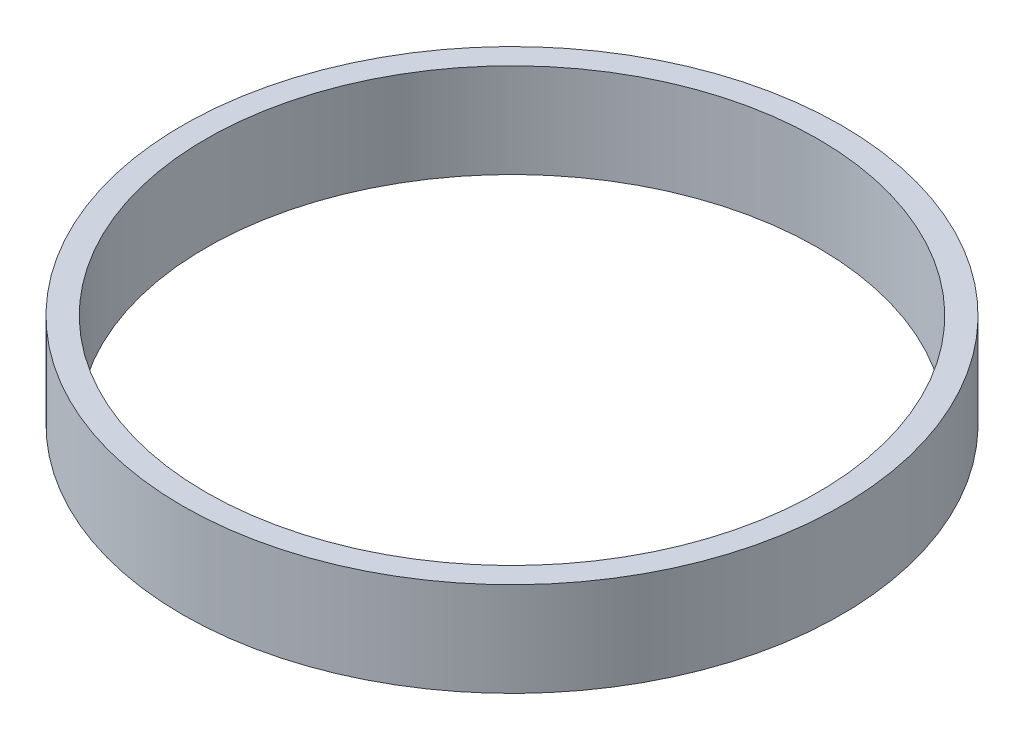
SolidWorks part; units mm, degrees
ref_plane "前视基准面" through (0, 0, 0) normal (0, 0, 1) x (1, 0, 0)
ref_plane "上视基准面" through (0, 0, 0) normal (0, 1, 0) x (1, 0, 0)
ref_plane "右视基准面" through (0, 0, 0) normal (1, 0, 0) x (0, 0, -1)
other "Configuration Table"
sketch "草图1" plane through (0, 0, 0) normal (0, 1, 0) x (1, 0, 0)
  line L0 (35, 0) -> (-35, 0) construction
  line L1 (-35, 0) -> (-32.5, 0)
  line L2 (32.5, 0) -> (35, 0)
  circle A0 centre (0, 0) radius 35
  circle A1 centre (0, 0) radius 32.5
  dimension "D1" = 70
  dimension "D2" = 65
extrude "凸台-拉伸1" add sketch "草图1" along normal blind 10 contours A1 L2 A0 L1 | A1 L1 A0 L2
